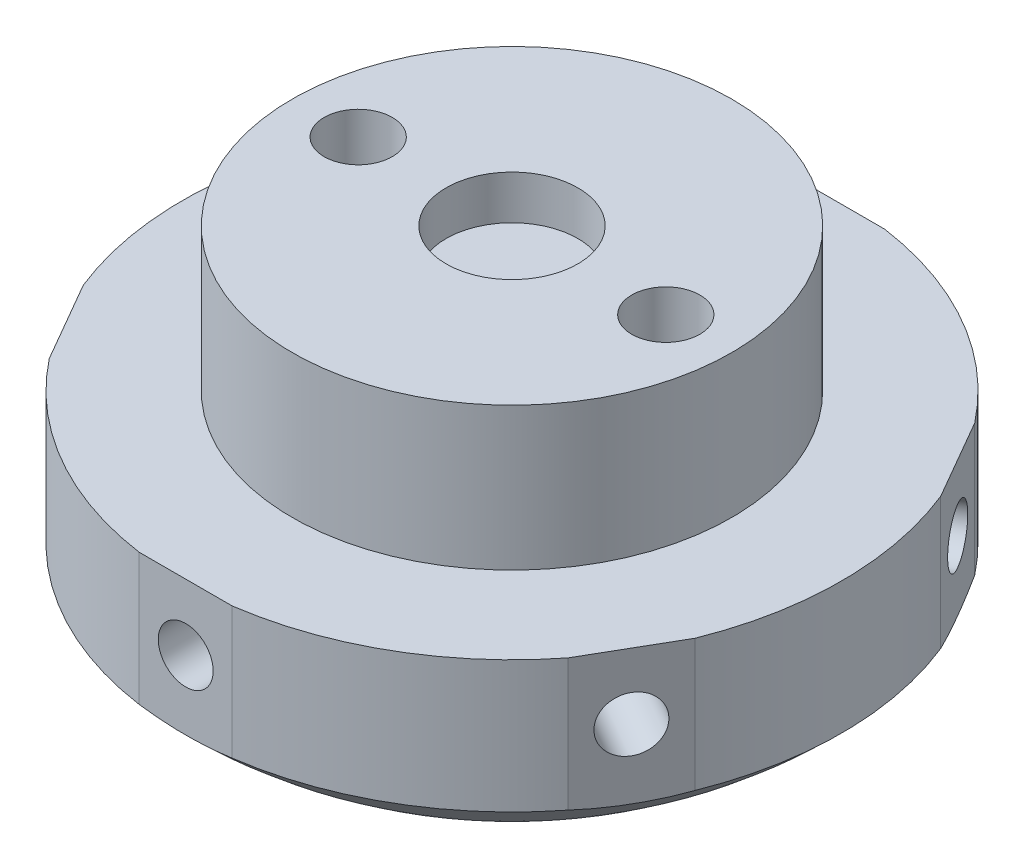
SolidWorks part; units mm, degrees
material "6061 合金"
ref_plane "前视基准面" through (0, 0, 0) normal (0, 0, 1) x (1, 0, 0)
ref_plane "上视基准面" through (0, 0, 0) normal (0, 1, 0) x (1, 0, 0)
ref_plane "右视基准面" through (0, 0, 0) normal (1, 0, 0) x (0, 0, -1)
sketch "草图1" plane through (0, 0, 0) normal (0, 1, 0) x (1, 0, 0)
  circle A0 centre (0, 0) radius 15
  dimension "D1" = 30
extrude "凸台-拉伸1" add sketch "草图1" along normal blind 6
sketch "草图2" plane through (0, 6, 0) normal (0, 1, 0) x (1, 0, 0)
  circle A0 centre (0, 0) radius 10
  dimension "D1" = 20
extrude "凸台-拉伸2" add sketch "草图2" along normal blind 6.5
sketch "草图4" plane through (0, 0, 0) normal (0, 0, 1) x (1, 0, 0)
  line L0 (0, 0) -> (0, -6.2132)
  line L3 (0, 0) -> (15, 0)
  arc A0 (15, 0) -> (0, -6.2132) centre (0, 15) cw
revolve "旋转1" add sketch "草图4" angle 360 about L0
sketch "草图5" plane through (0, 12.5, 0) normal (0, 1, 0) x (1, 0, 0)
  circle A0 centre (0, 0) radius 7 construction
  circle A3 centre (7, 0) radius 1.55
  circle A7 centre (-7, 0) radius 1.55
  point P22 (0, 0)
  dimension "D1" = 14
  dimension "D2" = 3.1
  dimension "D3" = 3.1
extrude "中心件固定孔" cut sketch "草图5" against normal through all
sketch3d "3D草图1" plane through (0, 0, 0) normal (0, 0, 1) x (1, 0, 0)
  dimension "D1" = 6.2
sketch "草图6" plane through (0, -6.2, 0) normal (0, 1, 0) x (1, 0, 0)
  circle A1 centre (0, 0) radius 7 construction
  circle A2 centre (-7, 0) radius 2.5
  circle A4 centre (7, 0) radius 2.5
  point P15 (0, 0)
  dimension "D1" = 5
  dimension "D2" = 5
extrude "沉头孔" cut sketch "草图6" along normal blind 3.7
sketch "草图9" plane through (0, 6, 0) normal (0, 1, 0) x (1, 0, 0)
  line L0 (0, 15) -> (0, 14.85) construction
  line L1 (11.8025, 9.2575) -> (13.9185, 5.5925)
  line L2 (-2.116, 14.85) -> (2.116, 14.85)
  line L3 (13.9185, -5.5925) -> (11.8025, -9.2575)
  line L4 (2.116, -14.85) -> (-2.116, -14.85)
  line L5 (-11.8025, -9.2575) -> (-13.9185, -5.5925)
  line L6 (-13.9185, 5.5925) -> (-11.8025, 9.2575)
  circle A0 centre (0, 0) radius 15 construction
  arc A1 (-11.8025, 9.2575) -> (-13.9185, 5.5925) centre (0, 0) ccw
  arc A2 (2.116, 14.85) -> (-2.116, 14.85) centre (0, 0) ccw
  arc A3 (13.9185, 5.5925) -> (11.8025, 9.2575) centre (0, 0) ccw
  arc A4 (11.8025, -9.2575) -> (13.9185, -5.5925) centre (0, 0) ccw
  arc A5 (-2.116, -14.85) -> (2.116, -14.85) centre (0, 0) ccw
  arc A6 (-13.9185, -5.5925) -> (-11.8025, -9.2575) centre (0, 0) ccw
  point P23 (0, 0)
  dimension "D1" = 6
extrude "切除-拉伸3" cut sketch "草图9" against normal through all
sketch "草图10" plane through (-12.8605, 0, -7.425) normal (-0.866, 0, -0.5) x (-0.5, 0, 0.866)
  line L0 (2.116, 6) -> (-2.116, 6) construction
  circle A0 centre (0, 3) radius 1.5
  dimension "D2" = 3
  dimension "D1" = 3
hole_wizard "M3 螺纹孔2" positions "3D草图4" profile "草图11" tap size "M3" standard "GB"
sketch3d "3D草图4"
  point P0 (-12.8605, 3, -7.425)
sketch "草图11" plane through (-12.8605, 3, -7.425) normal (0, 1, 0) x (-0.5, 0, 0.866)
  line L0 (0, 0) -> (0, 8.7511)
  line L1 (0, 8.7511) -> (1.25, 8)
  line L2 (1.25, 8) -> (1.25, 0)
  line L5 (1.25, 0) -> (0, 0)
  line L10 (0, 8.7511) -> (-1.25, 8) construction
  line L11 (0, -6.35) -> (0, 107.95) construction
  dimension "螺纹孔钻头直径" = 2.5
  dimension "螺纹孔钻头深度" = 8
  dimension "导头角度" = 118
cosmetic thread "孔螺蚊线1" parameters "D1"=7.5, "D2"=3
pattern_circular "阵列(圆周)1" count 6 over 360 about axis through (0, 6, 0) along (0, 1, 0) of "M3 螺纹孔2"
sketch "草图12" plane through (0, 12.5, 0) normal (0, 1, 0) x (1, 0, 0)
  circle A0 centre (0, 0) radius 3
  dimension "D1" = 6
extrude "切除-拉伸4" cut sketch "草图12" against normal blind 2
